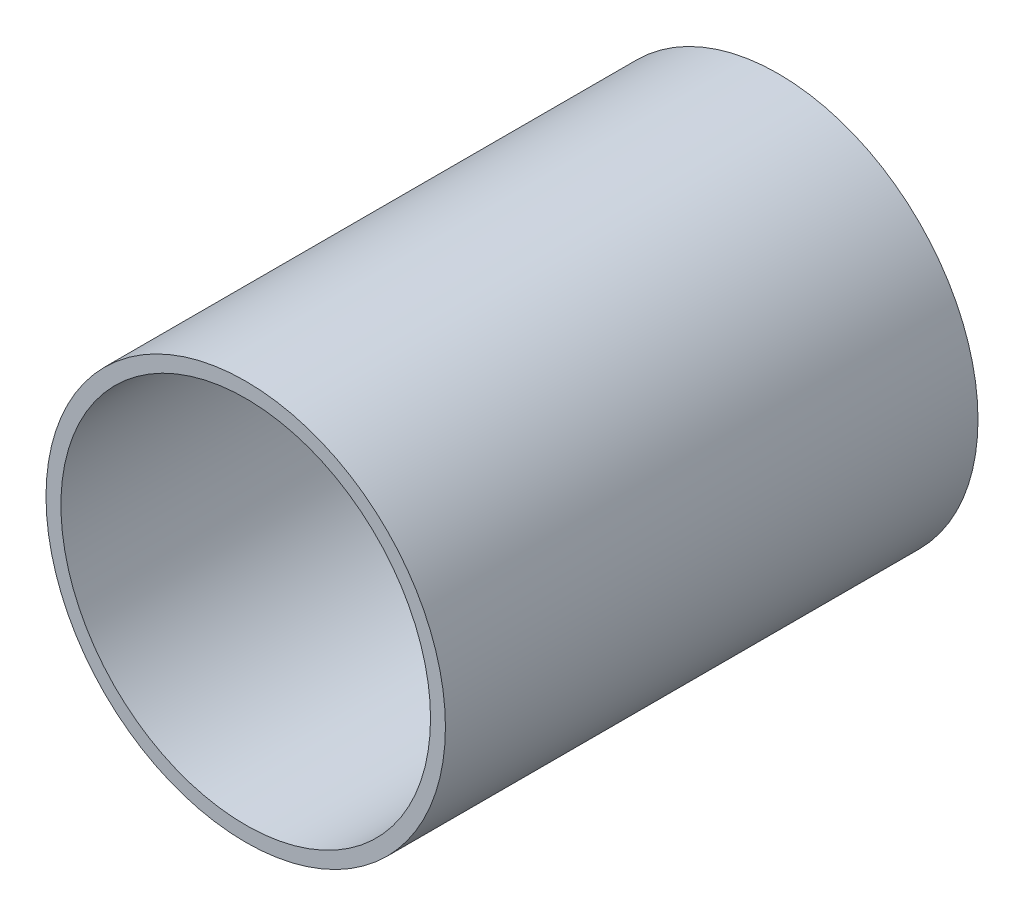
SolidWorks part; units mm, degrees
material "AISI 304"
ref_plane "Front" through (0, 0, 0) normal (0, 0, 1) x (1, 0, 0)
ref_plane "Top" through (0, 0, 0) normal (0, 1, 0) x (1, 0, 0)
ref_plane "Right" through (0, 0, 0) normal (1, 0, 0) x (0, 0, -1)
sketch "Sketch1" plane through (0, 0, 0) normal (0, 0, 1) x (1, 0, 0)
  circle A0 centre (0, 0) radius 9.525
  circle A1 centre (0, 0) radius 8.8138
  dimension "D1" = 19.05
  dimension "D2" = 17.6276
extrude "Boss-Extrude1" add sketch "Sketch1" along normal blind 25.4 contours A1
